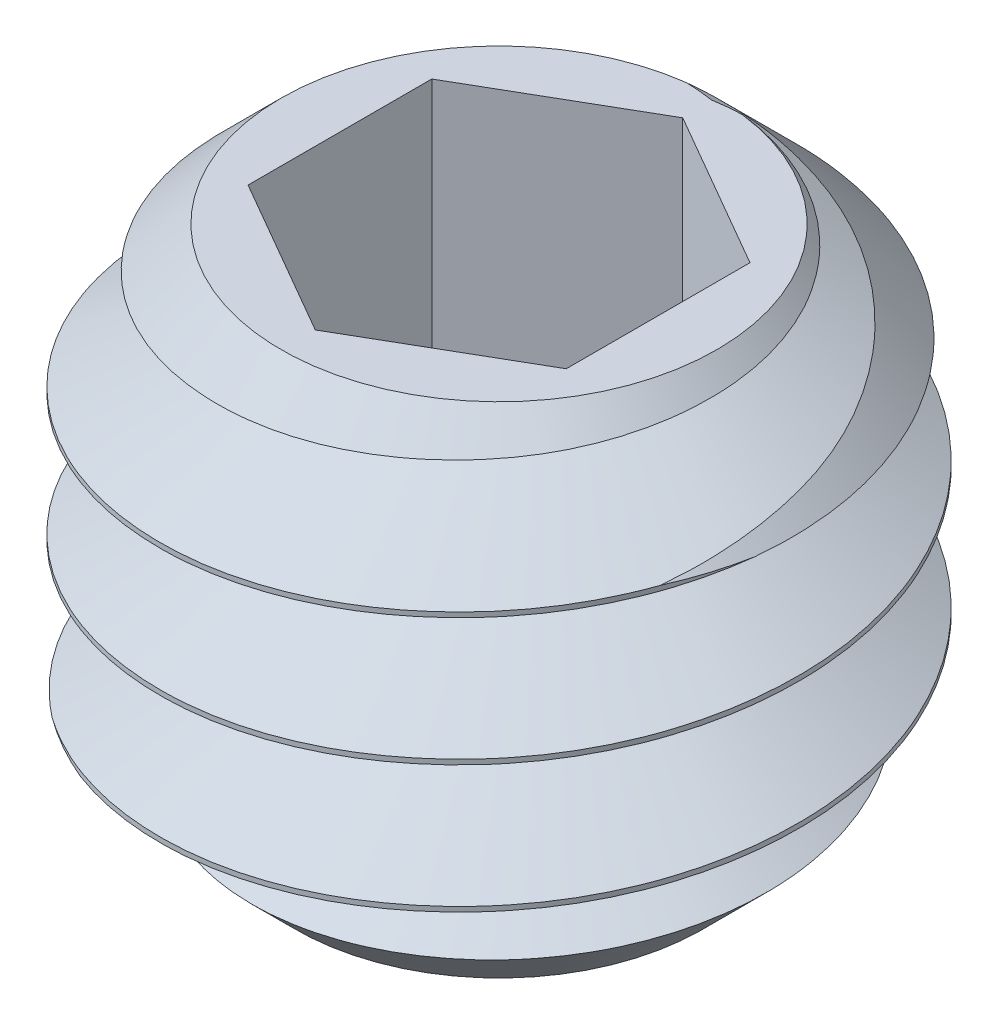
SolidWorks part; units mm, degrees
ref_plane "Front Plane" through (0, 0, 0) normal (0, 0, 1) x (1, 0, 0)
ref_plane "Top Plane" through (0, 0, 0) normal (0, 1, 0) x (1, 0, 0)
ref_plane "Right Plane" through (0, 0, 0) normal (1, 0, 0) x (0, 0, -1)
sketch "Sketch1" plane through (0, 0, 0) normal (0, 0, 1) x (1, 0, 0)
  line L0 (0, 0) -> (0, 54.6222) construction
  line L1 (0, 0.5866) -> (-1.016, 0)
  line L2 (-1.016, 0) -> (-1.27, 0)
  line L3 (-1.27, 0) -> (-1.9939, 0.7239)
  line L4 (-1.9939, 0.7239) -> (-1.9939, 2.54)
  line L5 (-1.9939, 2.54) -> (-1.3589, 3.175)
  line L6 (-1.3589, 3.175) -> (0, 3.175)
  line L7 (0, 3.175) -> (0, 0.5866)
  dimension "D1" = 60
  dimension "D2" = 2.032
  dimension "D3" = 135
  dimension "D4" = 135
  dimension "D5" = 0.635
  dimension "D6" = 3.9878
  dimension "D7" = 0.254
  dimension "D8" = 3.175
revolve "Revolve1" add sketch "Sketch1" angle 360 about L0
sketch "Sketch2" plane through (0, 3.175, 0) normal (0, 1, 0) x (1, 0, 0)
  line L0 (0, 0) -> (0, 1.3178) construction
  line L1 (0, 1.1457) -> (-0.9922, 0.5728)
  line L2 (-0.9922, 0.5728) -> (-0.9922, -0.5728)
  line L3 (-0.9922, -0.5728) -> (0, -1.1457)
  line L4 (0, -1.1457) -> (0.9922, -0.5728)
  line L5 (0.9922, -0.5728) -> (0.9922, 0.5728)
  line L6 (0.9922, 0.5728) -> (0, 1.1457)
  circle A0 centre (0, 0) radius 0.9922 construction
  dimension "D1" = 1.9844
extrude "Cut-Extrude1" cut sketch "Sketch2" against normal blind 1.778
sketch "Sketch3" plane through (0, 3.175, 0) normal (0, 1, 0) x (1, 0, 0)
  circle A0 centre (0, 0) radius 1.9939 construction
  circle A1 centre (0, 0) radius 1.9939
curve "Helix/Spiral1" pitch 0.795 height 9.525 turns 11.9808
sketch "Sketch4" plane through (0, 0, 0) normal (1, 0, 0) x (0, 0, -1)
  line L0 (-2.0193, 3.9687) -> (-2.0193, 3.175)
  line L1 (-2.0193, 3.175) -> (-1.3319, 3.5719)
  line L2 (-1.3319, 3.5719) -> (-2.0193, 3.9687)
  line L3 (-1.3319, 3.5719) -> (-2.0193, 3.5719) construction
  line L5 (-2.0193, 3.9687) -> (-1.3319, 4.3656) construction
  line L6 (-1.3319, 4.3656) -> (-2.0193, 4.7625) construction
  line L7 (-2.0193, 4.7625) -> (-2.0193, 3.9687) construction
  line L8 (1.3589, 3.175) -> (-1.3589, 3.175) construction
  line L10 (0, 3.175) -> (0, 10.7636) construction
  dimension "D1" = 60
  dimension "D2" = 0.7937
  dimension "D3" = 4.0386
sweep "Cut-Sweep3" cut profiles "Sketch4" path "Helix/Spiral1"
